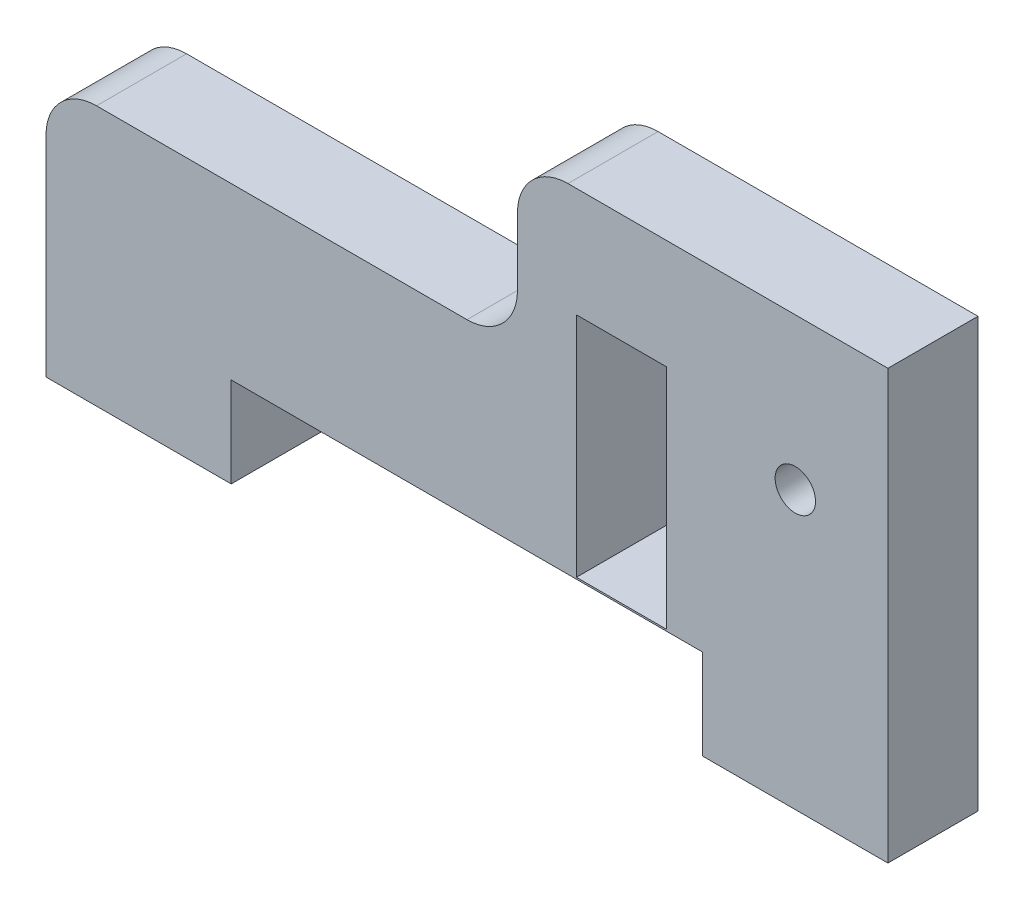
SolidWorks part; units mm, degrees
ref_plane "Front Plane" through (0, 0, 0) normal (0, 0, 1) x (1, 0, 0)
ref_plane "Top Plane" through (0, 0, 0) normal (0, 1, 0) x (1, 0, 0)
ref_plane "Right Plane" through (0, 0, 0) normal (1, 0, 0) x (0, 0, -1)
sketch "Model" plane through (0, 0, 0) normal (0, 0, 1) x (1, 0, 0)
  line L300 (31.5, 5.45) -> (31.5, 18.95)
  line L301 (36.85, 5.45) -> (31.5, 5.45)
  line L302 (36.85, 18.95) -> (36.85, 5.45)
  line L303 (31.5, 18.95) -> (36.85, 18.95)
  line L304 (3, 15.45) -> (25, 15.45)
  line L305 (28, 18.45) -> (28, 22.45)
  line L306 (0, 12.45) -> (0, 0)
  line L307 (50, 25.45) -> (31, 25.45)
  line L308 (50, 0) -> (50, 25.45)
  line L309 (39, 0) -> (50, 0)
  line L310 (39, 5.35) -> (39, 0)
  line L311 (11, 5.35) -> (39, 5.35)
  line L312 (11, 0) -> (11, 5.35)
  line L313 (0, 0) -> (11, 0)
  circle A42 centre (44.5, 16.45) radius 1.2
  arc A43 (3, 15.45) -> (0, 12.45) centre (3, 12.45) ccw
  arc A44 (25, 15.45) -> (28, 18.45) centre (25, 18.45) ccw
  arc A45 (31, 25.45) -> (28, 22.45) centre (31, 22.45) ccw
extrude "Boss-Extrude1" add sketch "Model" along normal blind 5.35
